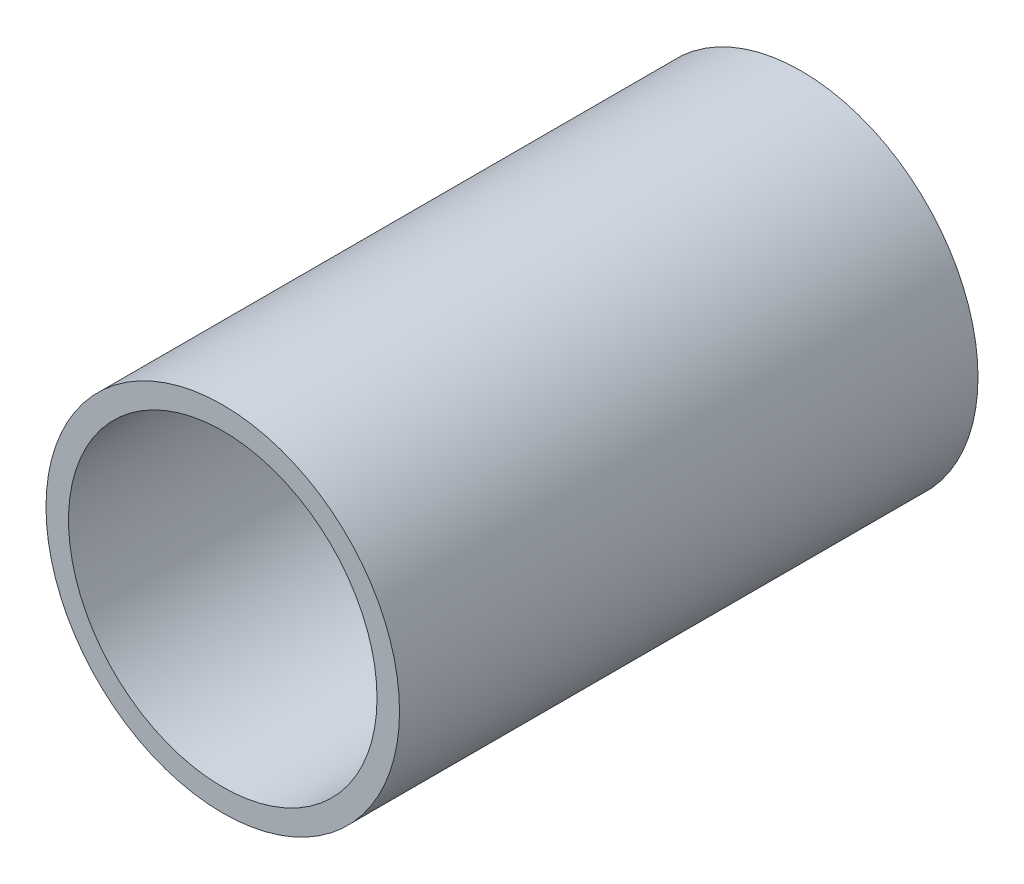
SolidWorks part; units mm, degrees
ref_plane "Front Plane" through (0, 0, 0) normal (0, 0, 1) x (1, 0, 0)
ref_plane "Top Plane" through (0, 0, 0) normal (0, 1, 0) x (1, 0, 0)
ref_plane "Right Plane" through (0, 0, 0) normal (1, 0, 0) x (0, 0, -1)
sketch "Sketch1" plane through (0, 0, 0) normal (0, 0, 1) x (1, 0, 0)
  circle A0 centre (0, 0) radius 19.2
  circle A1 centre (0, 0) radius 22
  dimension "D1" = 38.4
  dimension "D2" = 44
extrude "Boss-Extrude1" add sketch "Sketch1" along normal blind 72
